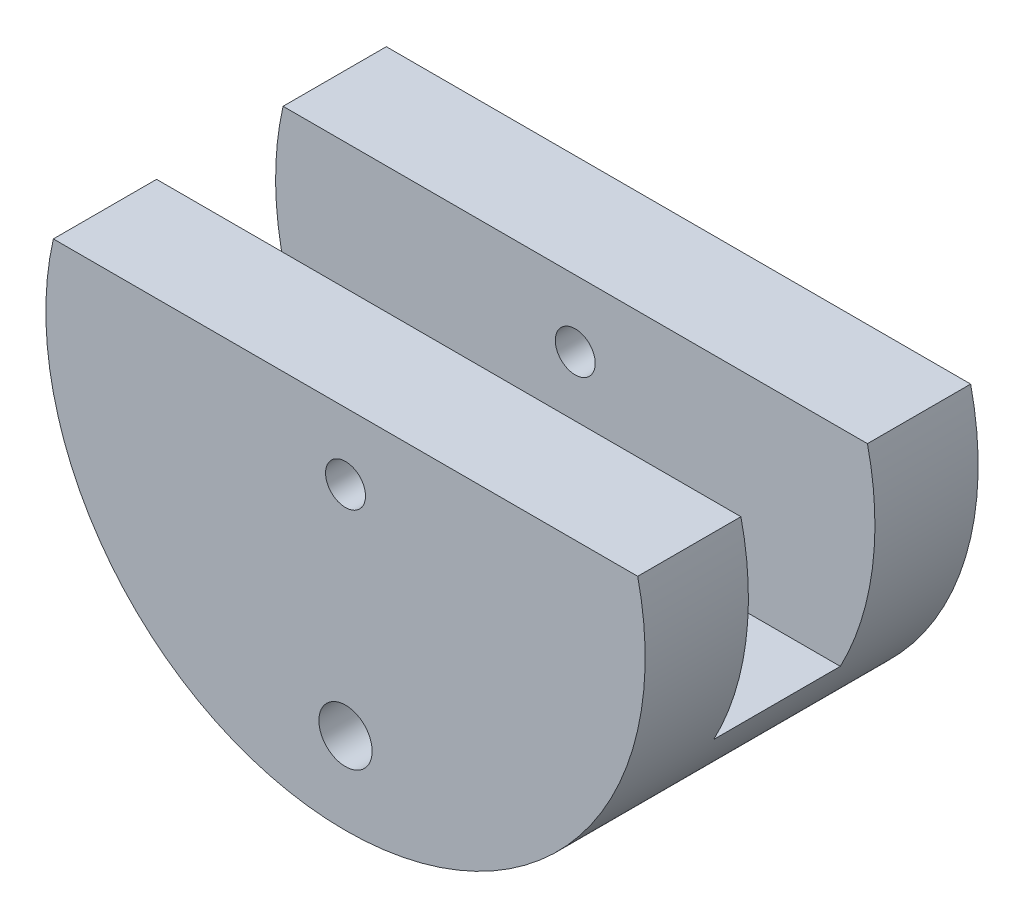
SolidWorks part; units mm, degrees
ref_plane "前视基准面" through (0, 0, 0) normal (0, 0, 1) x (1, 0, 0)
ref_plane "上视基准面" through (0, 0, 0) normal (0, 1, 0) x (1, 0, 0)
ref_plane "右视基准面" through (0, 0, 0) normal (1, 0, 0) x (0, 0, -1)
sketch "草图1" plane through (0, 0, 0) normal (0, 0, 1) x (1, 0, 0)
  line L1 (0, 13.5587) -> (0, -57.8806) construction
  line L2 (-62.0329, 10) -> (46.1939, 10) construction
  line L3 (-43.8748, 10) -> (43.8748, 10)
  circle A1 centre (0, -32.69) radius 4
  arc A2 (-43.8748, 10) -> (43.8748, 10) centre (0, 0) ccw
  circle A3 centre (0, 0) radius 3
  dimension "D1" = 90
  dimension "D3" = 8
  dimension "D4" = 10
  dimension "D2" = 6
  dimension "D5" = 32.69
extrude "凸台-拉伸1" add sketch "草图1" along normal mid plane 50
sketch "草图2" plane through (0, 0, 0) normal (0, 0, 1) x (1, 0, 0)
  line L1 (-53.1403, 20.9994) -> (53.1403, 20.9994)
  line L2 (-53.1403, 20.9994) -> (-53.1403, -20.9994)
  line L3 (-53.1403, -20.9994) -> (53.1403, -20.9994)
  line L4 (53.1403, 20.9994) -> (53.1403, -20.9994)
  line L5 (-53.1403, 20.9994) -> (53.1403, -20.9994) construction
  line L6 (-53.1403, -20.9994) -> (53.1403, 20.9994) construction
  point P0 (0, 0)
extrude "切除-拉伸1" cut sketch "草图2" against normal mid plane 19
sketch "草图3" plane through (0, 0, 0) normal (0, 0, 1) x (1, 0, 0)
  line L0 (-8.4, -32.69) -> (-8.4, -18.964)
  line L1 (-8.4, -18.964) -> (8.4, -18.964)
  line L2 (8.4, -18.964) -> (8.4, -32.69)
  arc A0 (-8.4, -32.69) -> (8.4, -32.69) centre (0, -32.69) ccw
  dimension "D1" = 16.8
extrude "切除-拉伸2" cut sketch "草图3" against normal mid plane 6
